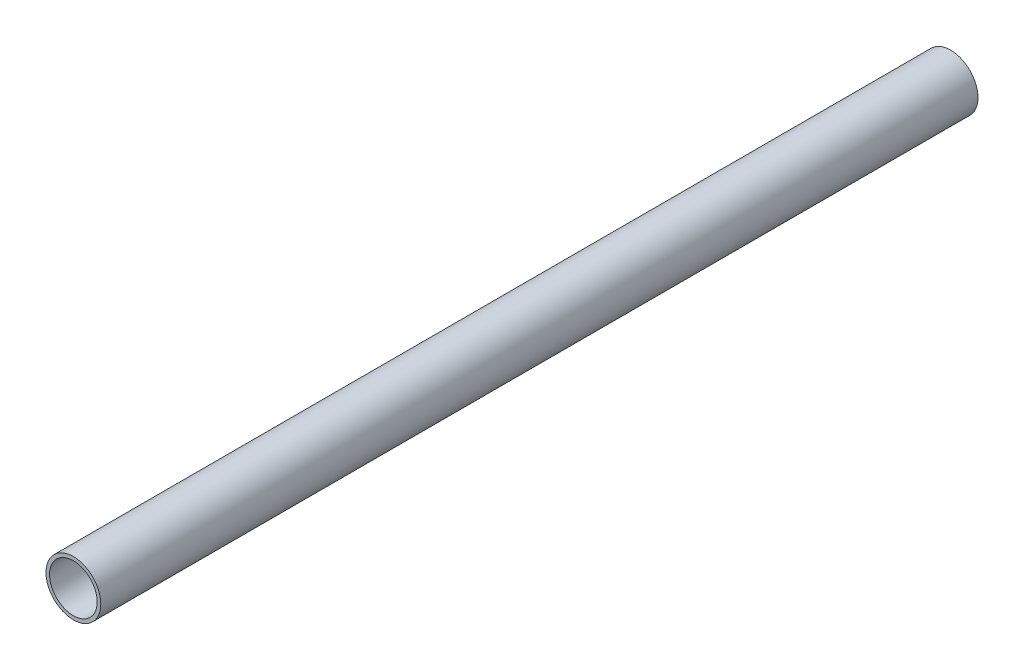
SolidWorks part; units mm, degrees
ref_plane "Front Plane" through (0, 0, 0) normal (0, 0, 1) x (1, 0, 0)
ref_plane "Top Plane" through (0, 0, 0) normal (0, 1, 0) x (1, 0, 0)
ref_plane "Right Plane" through (0, 0, 0) normal (1, 0, 0) x (0, 0, -1)
sketch "Sketch1" plane through (0, 0, 0) normal (0, 0, 1) x (1, 0, 0)
  line L0 (9.525, 0) -> (8.2804, 0) construction
  line L1 (-9.525, 0) -> (9.525, 0) construction
  dimension "OD" = 19.05
  dimension "Wall Thickness" = 1.2446
sketch "Sketch2" plane through (0, 0, 0) normal (1, 0, 0) x (0, 0, -1)
  line L0 (152.4, 0) -> (-152.4, 0)
  point P4 (0, 0)
  dimension "Length" = 304.8
sketch "Sketch3" plane through (0, 0, 0) normal (0, 0, 1) x (1, 0, 0)
  circle A0 centre (0, 0) radius 9.525
  circle A1 centre (0, 0) radius 8.2804
extrude "Boss-Extrude1" add sketch "Sketch3" along normal up to vertex (152.4 mm away) and the other way up to vertex (152.4 mm away) up to point (0, 0, 152.4) other way up to point (0, 0, -152.4)
